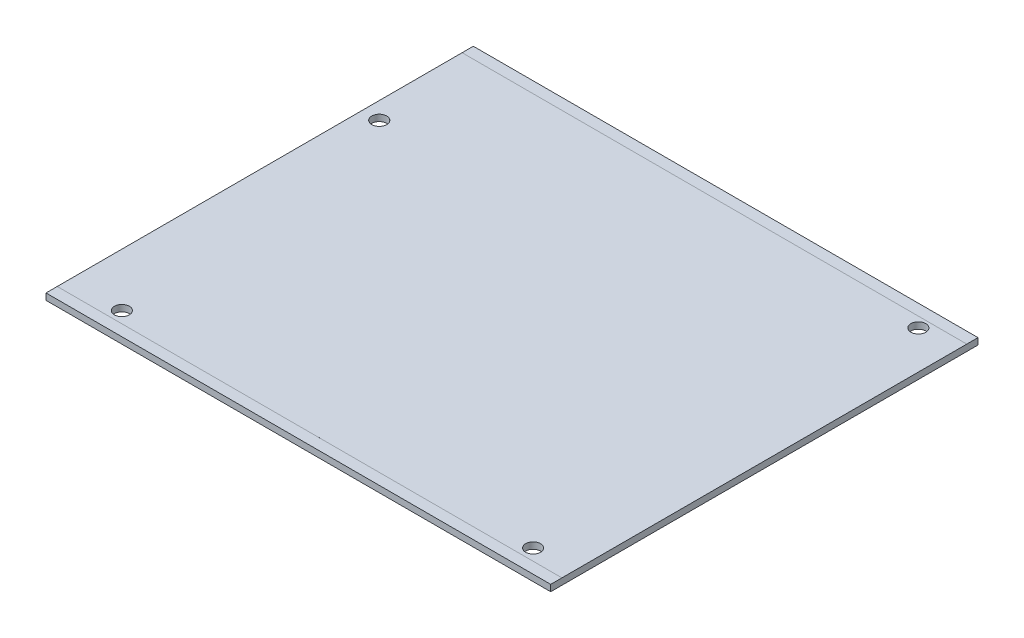
SolidWorks part; units mm, degrees
ref_plane "Front Plane" through (0, 0, 0) normal (0, 0, 1) x (1, 0, 0)
ref_plane "Top Plane" through (0, 0, 0) normal (0, 1, 0) x (1, 0, 0)
ref_plane "Right Plane" through (0, 0, 0) normal (1, 0, 0) x (0, 0, -1)
sketch "Sketch1" plane through (0, 0, 0) normal (0, 1, 0) x (1, 0, 0)
  line L1 (-67.5, -57.15) -> (67.5, -57.15)
  line L2 (-67.5, -57.15) -> (-67.5, 57.15)
  line L3 (-67.5, 57.15) -> (67.5, 57.15)
  line L4 (67.5, -57.15) -> (67.5, 57.15)
  line L5 (-67.5, -57.15) -> (67.5, 57.15) construction
  line L6 (-67.5, 57.15) -> (67.5, -57.15) construction
  point P0 (0, 0)
  dimension "D1" = 135
  dimension "D2" = 114.3
extrude "Boss-Extrude1" add sketch "Sketch1" along normal blind 1.724
sketch "Sketch3" plane through (0, 1.724, 0) normal (0, 1, 0) x (1, 0, 0)
  line L0 (67.5, -57.15) -> (67.5, 57.15) construction
  line L1 (-67.5, 57.15) -> (67.5, 57.15)
  line L2 (-67.5, 57.15) -> (-67.5, 54.15)
  line L3 (-67.5, 54.15) -> (67.5, 54.15)
  line L4 (67.5, 57.15) -> (67.5, 54.15)
  line L6 (-67.5, -57.15) -> (67.5, -57.15)
  line L7 (-67.5, -57.15) -> (-67.5, -54.15)
  line L8 (-67.5, -54.15) -> (67.5, -54.15)
  line L9 (67.5, -57.15) -> (67.5, -54.15)
  dimension "D1" = 3
  dimension "D2" = 3
extrude "Cut-Extrude2" cut sketch "Sketch3" against normal blind 0.0001
sketch "Sketch4" plane through (0, 0, 0) normal (0, -1, 0) x (1, 0, 0)
  circle A0 centre (-53.2755, 51.0798) radius 2
  circle A1 centre (56.7245, 51.0798) radius 2
  circle A2 centre (57.2725, -51.4202) radius 2
  circle A3 centre (-62.9275, -27.4202) radius 2
  dimension "D1" = 4
  dimension "D2" = 4
  dimension "D3" = 4
  dimension "D4" = 4
extrude "Cut-Extrude3" cut sketch "Sketch4" against normal through all
